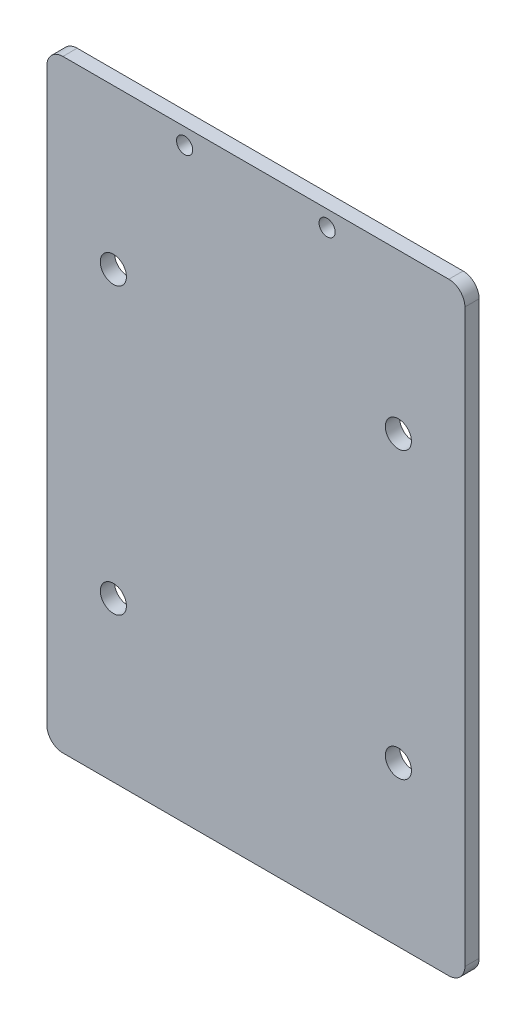
SolidWorks part; units mm, degrees
ref_plane "Plan de face" through (0, 0, 0) normal (0, 0, 1) x (1, 0, 0)
ref_plane "Plan de dessus" through (0, 0, 0) normal (0, 1, 0) x (1, 0, 0)
ref_plane "Plan de droite" through (0, 0, 0) normal (1, 0, 0) x (0, 0, -1)
sketch "Sketch1" plane through (0, 0, 0) normal (0, 0, 1) x (1, 0, 0)
  line L0 (44, -60.12) -> (44, 60.12)
  line L1 (40.62, 63.5) -> (-40.62, 63.5)
  line L2 (-44, 60.12) -> (-44, -60.12)
  line L3 (-40.62, -63.5) -> (40.62, -63.5)
  circle A0 centre (-30, 30) radius 2.75
  circle A1 centre (30, 30) radius 2.75
  circle A2 centre (-30, -30) radius 2.75
  circle A3 centre (30, -30) radius 2.75
  arc A4 (40.62, -63.5) -> (44, -60.12) centre (40.62, -60.12) ccw
  arc A5 (44, 60.12) -> (40.62, 63.5) centre (40.62, 60.12) ccw
  arc A6 (-40.62, 63.5) -> (-44, 60.12) centre (-40.62, 60.12) ccw
  arc A7 (-44, -60.12) -> (-40.62, -63.5) centre (-40.62, -60.12) ccw
  circle A8 centre (15, 60.11) radius 1.7
  circle A9 centre (-15, 60.11) radius 1.7
  dimension "D1" = 5.5
  dimension "D2" = 5.5
  dimension "D3" = 5.5
  dimension "D4" = 5.5
  dimension "D5" = 3.4
  dimension "D6" = 3.4
extrude "Boss-Extrude1" add sketch "Sketch1" along normal blind 3
